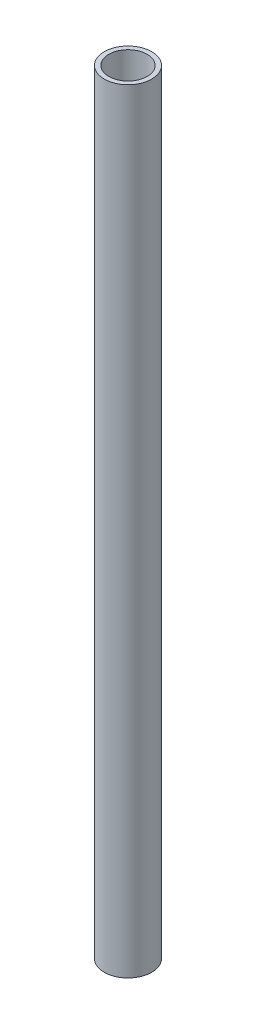
SolidWorks part; units mm, degrees
material "AISI 4130 Steel, annealed at 865C"
ref_plane "X-Y Datum" through (0, 0, 0) normal (0, 0, 1) x (1, 0, 0)
ref_plane "X-Z Datum" through (0, 0, 0) normal (0, 1, 0) x (1, 0, 0)
ref_plane "Y-Z Datum" through (0, 0, 0) normal (1, 0, 0) x (0, 0, -1)
sketch "Sketch1" plane through (0, 0, 0) normal (0, 1, 0) x (1, 0, 0)
  circle A0 centre (0, 0) radius 12.7
  dimension "D1" = 25.4
extrude "Boss-Extrude1" add sketch "Sketch1" along normal blind 414.02
shell "Shell1" thickness 2.413
sketch "Sketch2" plane through (0, 2.413, 0) normal (0, 1, 0) x (1, 0, 0)
  circle A1 centre (0, 0) radius 10.287
  circle A2 centre (0, 0) radius 10.287
  dimension "D1" = 0
extrude "Cut-Extrude1" cut sketch "Sketch2" against normal through all
